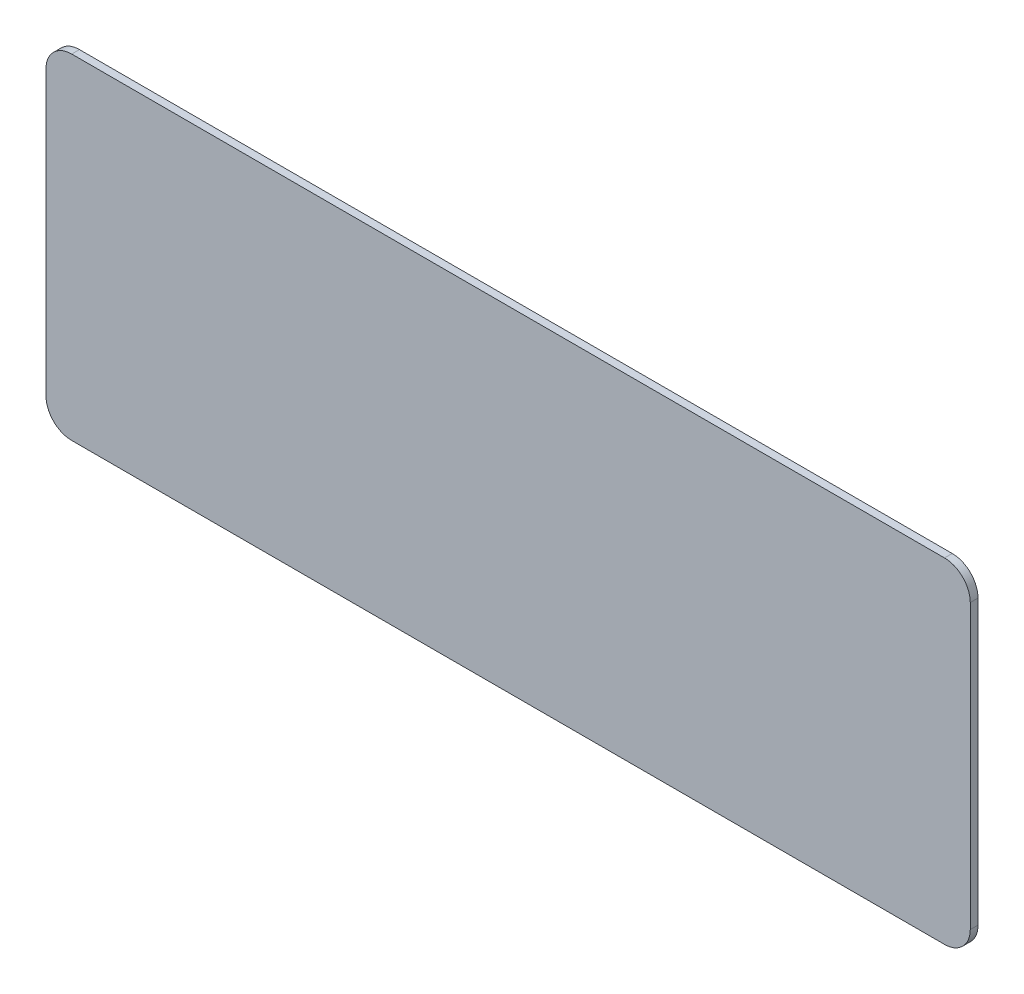
SolidWorks part; units mm, degrees
ref_plane "Front Plane" through (0, 0, 0) normal (0, 0, 1) x (1, 0, 0)
ref_plane "Top Plane" through (0, 0, 0) normal (0, 1, 0) x (1, 0, 0)
ref_plane "Right Plane" through (0, 0, 0) normal (1, 0, 0) x (0, 0, -1)
sketch "Sketch1" plane through (0, 0, 0) normal (0, 0, 1) x (1, 0, 0)
  line L1 (-179.5, 65) -> (179.5, 65)
  line L2 (-179.5, 65) -> (-179.5, -65)
  line L3 (-179.5, -65) -> (179.5, -65)
  line L4 (179.5, 65) -> (179.5, -65)
  line L5 (-179.5, 65) -> (179.5, -65) construction
  line L6 (-179.5, -65) -> (179.5, 65) construction
  point P0 (0, 0)
  dimension "D1" = 359
  dimension "D2" = 130
extrude "Boss-Extrude1" add sketch "Sketch1" along normal blind 3
fillet "Fillet1" radius 10 4 edges at (-179.5, 65, 1.5) (179.5, 65, 1.5) (179.5, -65, 1.5) (-179.5, -65, 1.5)
